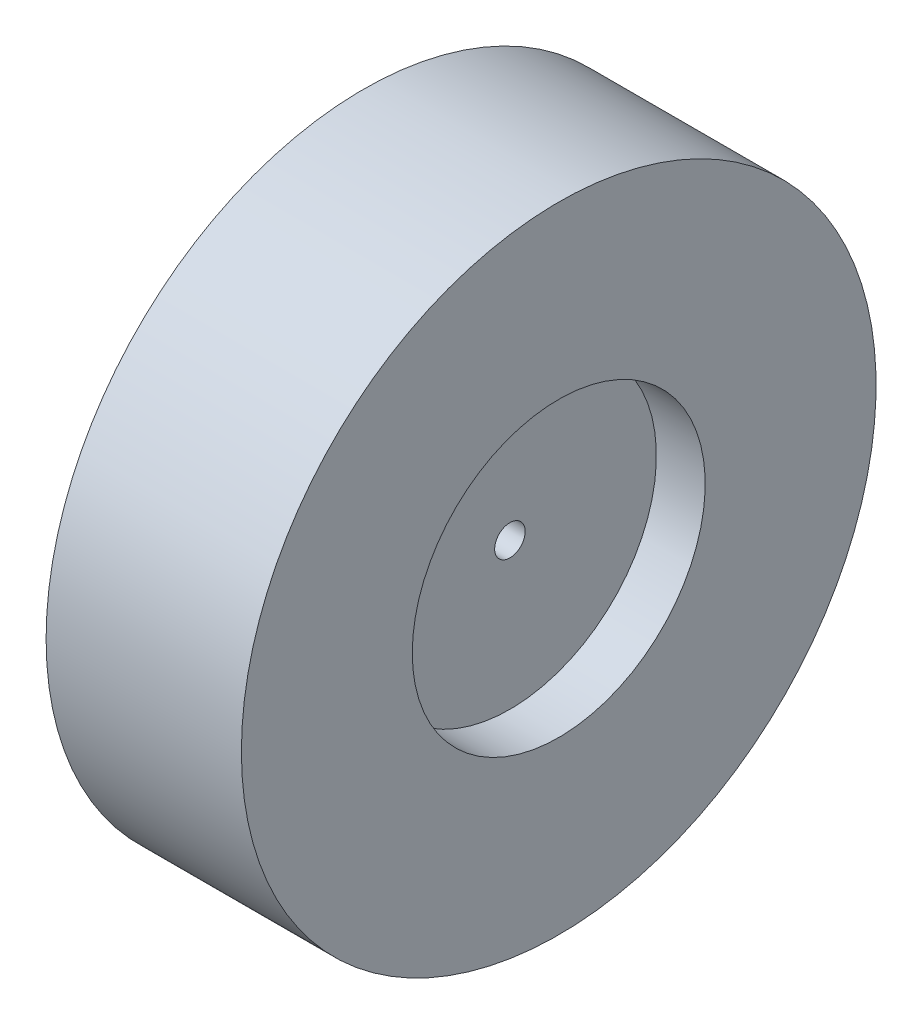
SolidWorks part; units mm, degrees
ref_plane "Front Plane" through (0, 0, 0) normal (0, 0, 1) x (1, 0, 0)
ref_plane "Top Plane" through (0, 0, 0) normal (0, 1, 0) x (1, 0, 0)
ref_plane "Right Plane" through (0, 0, 0) normal (1, 0, 0) x (0, 0, -1)
sketch "Sketch1" plane through (0, 0, 0) normal (0, 1, 0) x (1, 0, 0)
  line L0 (-50.8, 76.2) -> (-50.8, 165.1)
  line L1 (-25.4, 0) -> (25.4, 0) construction
  line L3 (-50.8, 165.1) -> (50.8, 165.1)
  line L4 (50.8, 76.2) -> (50.8, 165.1)
  line L7 (50.8, 76.2) -> (25.4, 76.2)
  line L8 (25.4, 7.9375) -> (25.4, 76.2)
  line L9 (-50.8, 76.2) -> (-25.4, 76.2)
  line L10 (-25.4, 7.9375) -> (-25.4, 76.2)
  line L11 (-25.4, 7.9375) -> (25.4, 7.9375)
  point P0 (0, 0)
  point P2 (0, 0)
  point P5 (0, 165.1)
  dimension "D1" = 76.2
  dimension "D2" = 50.8
  dimension "D3" = 101.6
  dimension "D4" = 165.1
  dimension "D5" = 7.9375
revolve "Revolve1" add sketch "Sketch1" angle 360 about L1
